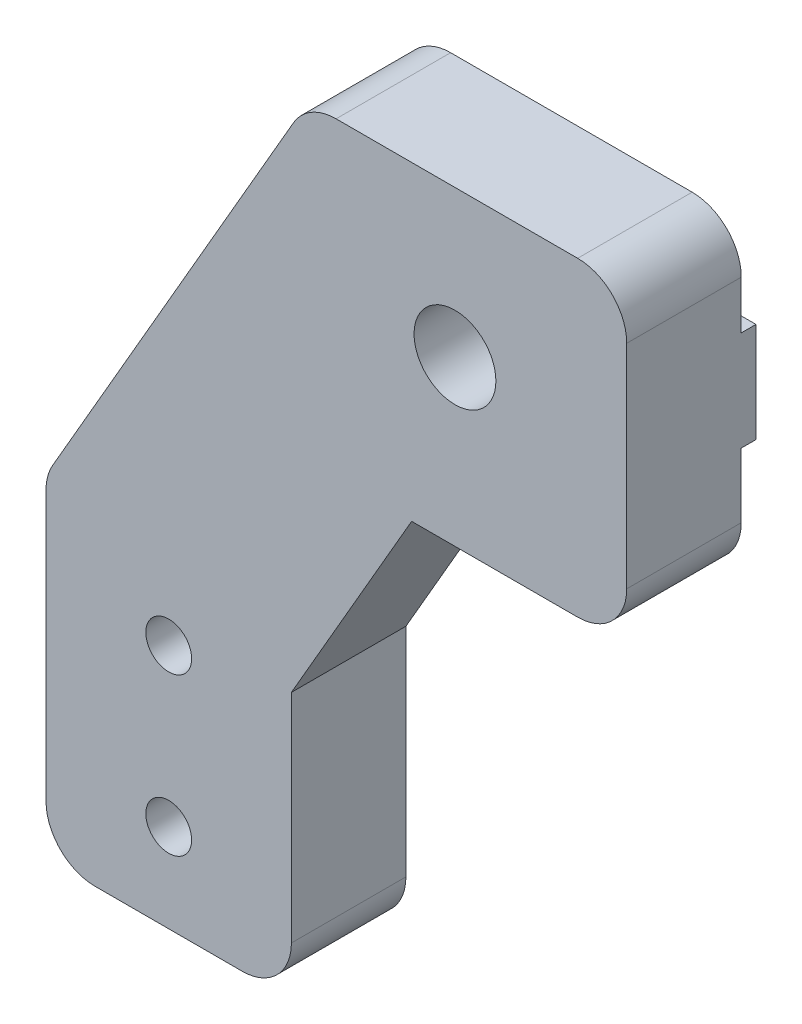
SolidWorks part; units mm, degrees
material "ABS"
ref_plane "Front Plane" through (0, 0, 0) normal (0, 0, 1) x (1, 0, 0)
ref_plane "Top Plane" through (0, 0, 0) normal (0, 1, 0) x (1, 0, 0)
ref_plane "Right Plane" through (0, 0, 0) normal (1, 0, 0) x (0, 0, -1)
sketch "Sketch1" plane through (0, 0, 0) normal (0, 0, 1) x (1, 0, 0)
  line L0 (3, 0) -> (12, 0)
  line L1 (15, 3) -> (15, 16.2679)
  line L2 (22.3509, 29) -> (32.5, 29)
  line L4 (32.5, 48) -> (17.7321, 48)
  line L5 (0, 19.4833) -> (0, 3)
  line L7 (15, 16.2679) -> (22.3509, 29)
  line L8 (7.5, 0) -> (7.5, 48) construction
  line L9 (15.134, 46.5) -> (0.4019, 20.9833)
  line L10 (35.5, 32) -> (35.5, 45)
  circle A0 centre (25, 39) radius 2.5
  arc A1 (35.5, 32) -> (32.5, 29) centre (32.5, 32) cw
  circle A2 centre (7.5, 5.4) radius 1.4
  circle A3 centre (7.5, 15) radius 1.4
  arc A4 (35.5, 45) -> (32.5, 48) centre (32.5, 45) ccw
  arc A7 (0, 19.4833) -> (0.4019, 20.9833) centre (3, 19.4833) cw
  arc A8 (0, 3) -> (3, 0) centre (3, 3) ccw
  arc A9 (12, 0) -> (15, 3) centre (12, 3) ccw
  arc A10 (15.134, 46.5) -> (17.7321, 48) centre (17.7321, 45) cw
  point P32 (0, 48)
  point P35 (0, 0)
  point P38 (15, 0)
  point P41 (16, 48)
  dimension "D5" = 5
  dimension "D6" = 19
  dimension "D7" = 25
  dimension "D8" = 3
  dimension "D10" = 2.8
  dimension "D11" = 2.8
  dimension "D12" = 5.4
  dimension "D13" = 9.6
  dimension "D14" = 15
  dimension "D18" = 3
  dimension "D19" = 3
  dimension "D1" = 48
  dimension "D2" = 15
  dimension "D3" = 9
  dimension "D4" = 28
  dimension "D16" = 120
  dimension "D17" = 16
extrude "Boss-Extrude1" add sketch "Sketch1" along normal blind 7
sketch "Sketch2" plane through (35.5, 0, 0) normal (1, 0, 0) x (0, 0, -1)
  line L1 (0, 42.05) -> (0.9, 42.05)
  line L2 (0, 42.05) -> (0, 35.95)
  line L3 (0, 35.95) -> (0.9, 35.95)
  line L4 (0.9, 42.05) -> (0.9, 35.95)
  line L6 (0.9, 39) -> (-7, 39) construction
  line L7 (-7, 32) -> (-7, 45) construction
  line L8 (0, 32) -> (0, 45) construction
  dimension "D1" = 6.1
  dimension "D2" = 0.9
extrude "Boss-Extrude2" add sketch "Sketch2" against normal up to surface (22.9352 mm away) contours L3 L4 L1 L2
sketch "Sketch3" plane through (0, 0, 0) normal (0, 0, 1) x (1, 0, 0)
  circle A0 centre (25, 39) radius 2.5 construction
  circle A2 centre (25, 39) radius 2.5
extrude "Cut-Extrude1" cut sketch "Sketch3" against normal up to next
